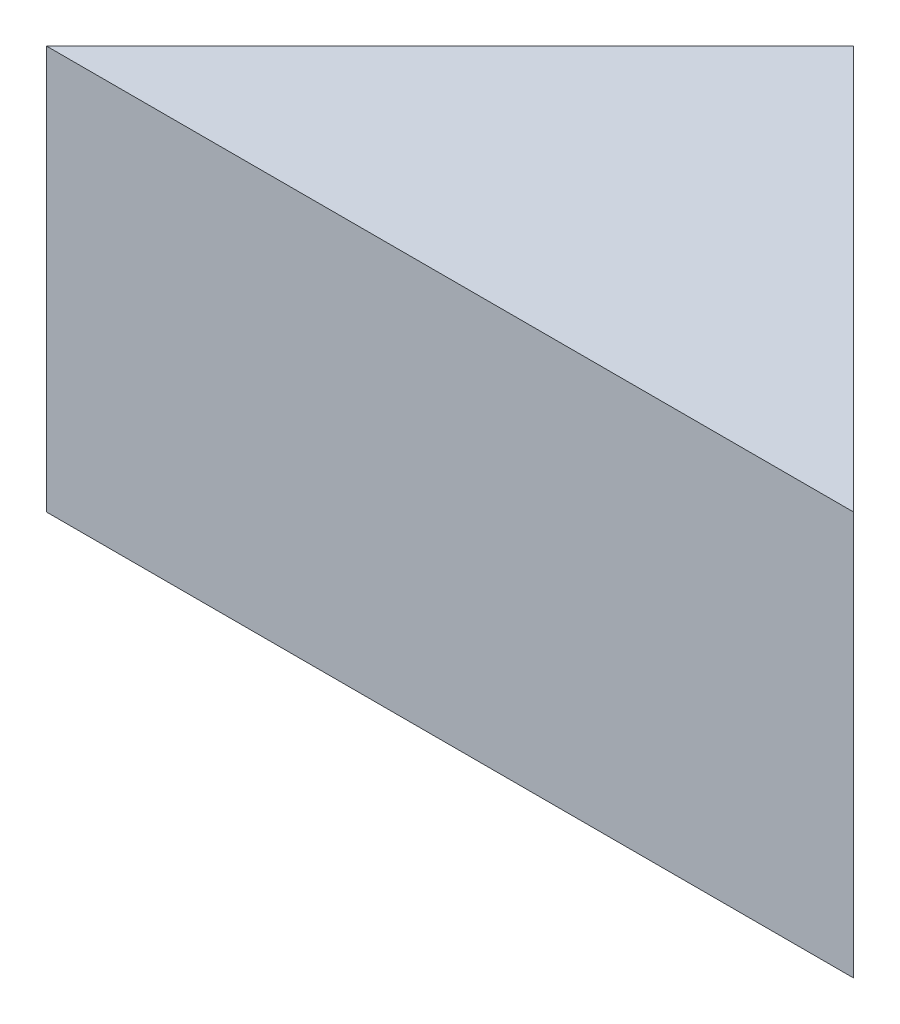
SolidWorks part; units mm, degrees
ref_plane "Přední rovina" through (0, 0, 0) normal (0, 0, 1) x (1, 0, 0)
ref_plane "Horní rovina" through (0, 0, 0) normal (0, 1, 0) x (1, 0, 0)
ref_plane "Pravá rovina" through (0, 0, 0) normal (1, 0, 0) x (0, 0, -1)
sketch "Sketch1" plane through (0, 0, 0) normal (0, 1, 0) x (1, 0, 0)
  line L0 (-20, 0) -> (20, 0)
  line L1 (20, 0) -> (0, 20)
  line L2 (0, 20) -> (0, 0) construction
  line L3 (-20, 0) -> (0, 20)
  point P4 (0, 0)
  point P5 (0, 0)
  point P6 (0, 16.8591)
  dimension "D1" = 45
  dimension "D2" = 20
extrude "Boss-Extrude1" add sketch "Sketch1" along normal blind 20 contours L2 L3 L0 | L1 L2 L0
equation "\"ěé\"=30"
